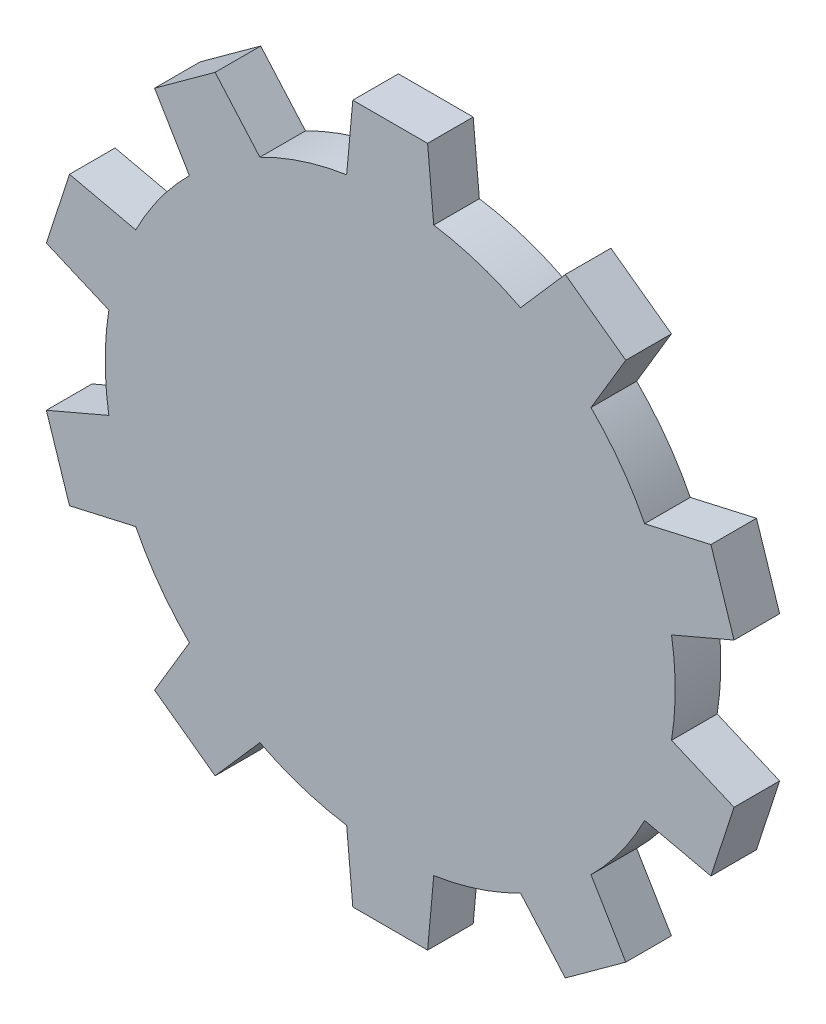
SolidWorks part; units mm, degrees
ref_plane "Alzado" through (0, 0, 0) normal (0, 0, 1) x (1, 0, 0)
ref_plane "Planta" through (0, 0, 0) normal (0, 1, 0) x (1, 0, 0)
ref_plane "Vista lateral" through (0, 0, 0) normal (1, 0, 0) x (0, 0, -1)
sketch "Croquis1" plane through (0, 0, 0) normal (0, 0, 1) x (1, 0, 0)
  line L0 (0, -1000) -> (0, 49000) construction
  line L1 (-1.9097, 12.3533) -> (-1.6399, 15.3209)
  line L2 (5.7161, 11.1165) -> (7.6786, 13.3588)
  line L3 (10.3321, 11.4309) -> (7.6786, 13.3588)
  line L4 (1.6399, 15.3209) -> (-1.6399, 15.3209)
  line L5 (8.8061, 8.8715) -> (10.3321, 11.4309)
  line L6 (0, 12.5) -> (-2.1399, 15.3209) construction
  line L7 (2.1399, 15.3209) -> (0, 12.5) construction
  line L8 (1.9097, 12.3533) -> (1.6399, 15.3209)
  line L9 (11.1585, 5.6336) -> (14.0642, 6.2941)
  line L10 (15.0778, 3.1747) -> (14.0642, 6.2941)
  line L11 (12.3388, 2.0011) -> (15.0778, 3.1747)
  line L12 (12.3388, -2.0011) -> (15.0778, -3.1747)
  line L13 (14.0642, -6.2941) -> (15.0778, -3.1747)
  line L14 (11.1585, -5.6336) -> (14.0642, -6.2941)
  line L15 (8.8061, -8.8715) -> (10.3321, -11.4309)
  line L16 (7.6786, -13.3588) -> (10.3321, -11.4309)
  line L17 (5.7161, -11.1165) -> (7.6786, -13.3588)
  line L18 (1.9097, -12.3533) -> (1.6399, -15.3209)
  line L19 (-1.6399, -15.3209) -> (1.6399, -15.3209)
  line L20 (-1.9097, -12.3533) -> (-1.6399, -15.3209)
  line L21 (-5.7161, -11.1165) -> (-7.6786, -13.3588)
  line L22 (-10.3321, -11.4309) -> (-7.6786, -13.3588)
  line L23 (-8.8061, -8.8715) -> (-10.3321, -11.4309)
  line L24 (-11.1585, -5.6336) -> (-14.0642, -6.2941)
  line L25 (-15.0778, -3.1747) -> (-14.0642, -6.2941)
  line L26 (-12.3388, -2.0011) -> (-15.0778, -3.1747)
  line L27 (-12.3388, 2.0011) -> (-15.0778, 3.1747)
  line L28 (-14.0642, 6.2941) -> (-15.0778, 3.1747)
  line L29 (-11.1585, 5.6336) -> (-14.0642, 6.2941)
  line L30 (-8.8061, 8.8715) -> (-10.3321, 11.4309)
  line L31 (-7.6786, 13.3588) -> (-10.3321, 11.4309)
  line L32 (-5.7161, 11.1165) -> (-7.6786, 13.3588)
  arc A0 (-12.3388, 2.0011) -> (-12.3388, -2.0011) centre (0, 0) ccw
  arc A1 (-8.8061, 8.8715) -> (-11.1585, 5.6336) centre (0, 0) ccw
  arc A2 (-11.1585, -5.6336) -> (-8.8061, -8.8715) centre (0, 0) ccw
  arc A3 (-5.7161, -11.1165) -> (-1.9097, -12.3533) centre (0, 0) ccw
  arc A4 (1.9097, -12.3533) -> (5.7161, -11.1165) centre (0, 0) ccw
  arc A5 (8.8061, -8.8715) -> (11.1585, -5.6336) centre (0, 0) ccw
  arc A6 (12.3388, -2.0011) -> (12.3388, 2.0011) centre (0, 0) ccw
  arc A7 (11.1585, 5.6336) -> (8.8061, 8.8715) centre (0, 0) ccw
  arc A8 (5.7161, 11.1165) -> (1.9097, 12.3533) centre (0, 0) ccw
  arc A9 (-1.9097, 12.3533) -> (-5.7161, 11.1165) centre (0, 0) ccw
  point P2 (0, 12.5)
  point P51 (0, 0)
  dimension "D1" = 10
  dimension "D2" = 0.5
  dimension "D4" = 0.5
extrude "Saliente-Extruir1" add sketch "Croquis1" along normal blind 2
sketch "Croquis2" plane through (0, 0, 0) normal (0, 0, -1) x (-1, 0, 0)
  line L0 (0, -1000) -> (0, 49000) construction
